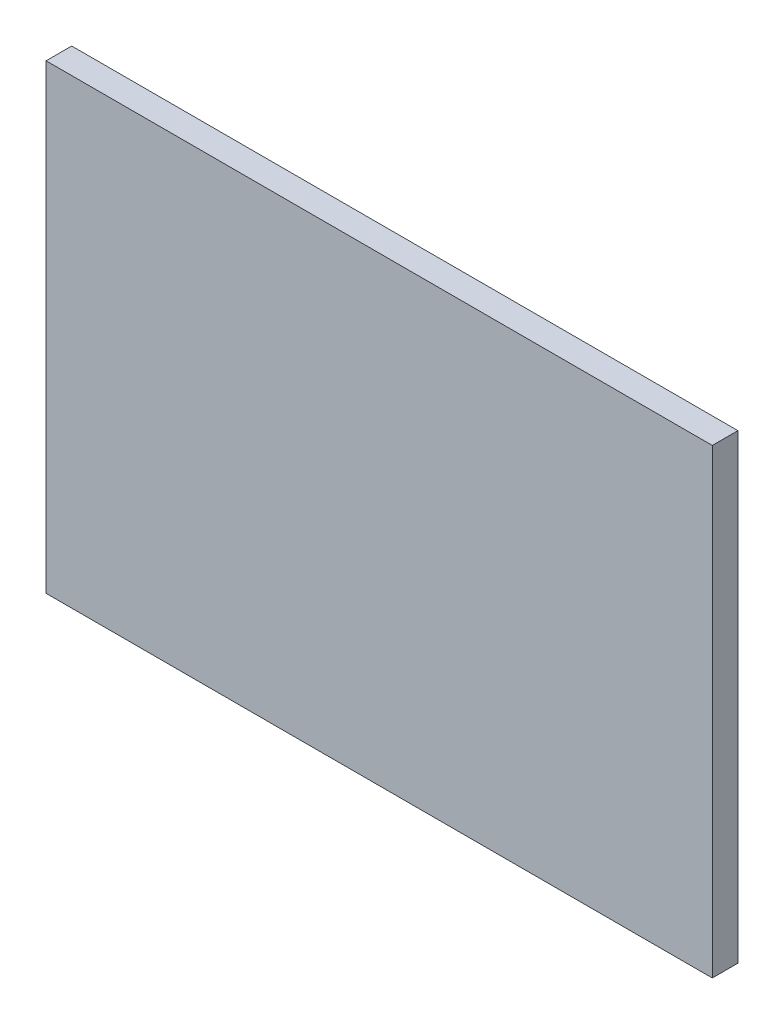
SolidWorks part; units mm, degrees
ref_plane "Спереди" through (0, 0, 0) normal (0, 0, 1) x (1, 0, 0)
ref_plane "Сверху" through (0, 0, 0) normal (0, 1, 0) x (1, 0, 0)
ref_plane "Справа" through (0, 0, 0) normal (1, 0, 0) x (0, 0, -1)
sketch "Эскиз1" plane through (0, 0, 0) normal (0, 0, 1) x (1, 0, 0)
  line L1 (-13, -9) -> (13, -9)
  line L2 (-13, -9) -> (-13, 9)
  line L3 (-13, 9) -> (13, 9)
  line L4 (13, -9) -> (13, 9)
  line L5 (-13, -9) -> (13, 9) construction
  line L6 (-13, 9) -> (13, -9) construction
  point P0 (0, 0)
  dimension "D1" = 26
  dimension "D2" = 18
extrude "Бобышка-Вытянуть1" add sketch "Эскиз1" against normal blind 1
